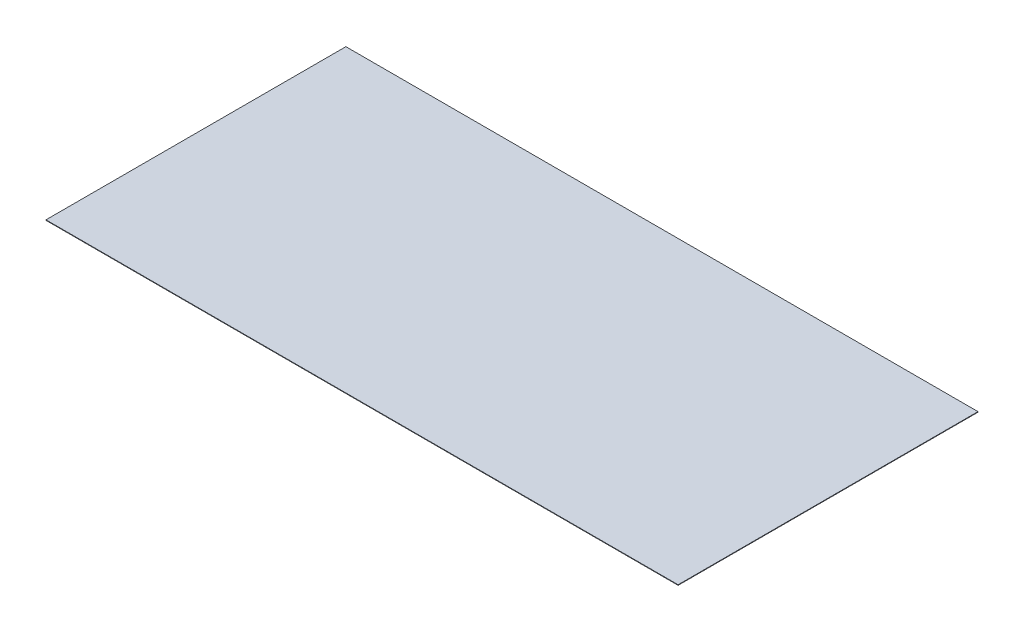
SolidWorks part; units mm, degrees
ref_plane "Front Plane" through (0, 0, 0) normal (0, 0, 1) x (1, 0, 0)
ref_plane "Top Plane" through (0, 0, 0) normal (0, 1, 0) x (1, 0, 0)
ref_plane "Right Plane" through (0, 0, 0) normal (1, 0, 0) x (0, 0, -1)
sketch "Sketch1" plane through (0, 0, 0) normal (0, 1, 0) x (1, 0, 0)
  line L1 (546.8095, -145.3855) -> (-703.1905, -145.3855)
  line L2 (546.8095, -145.3855) -> (546.8095, 447.6145)
  line L3 (546.8095, 447.6145) -> (-703.1905, 447.6145)
  line L4 (-703.1905, -145.3855) -> (-703.1905, 447.6145)
  dimension "D1" = 1250
  dimension "D2" = 593
extrude "Boss-Extrude1" add sketch "Sketch1" along normal blind 1
